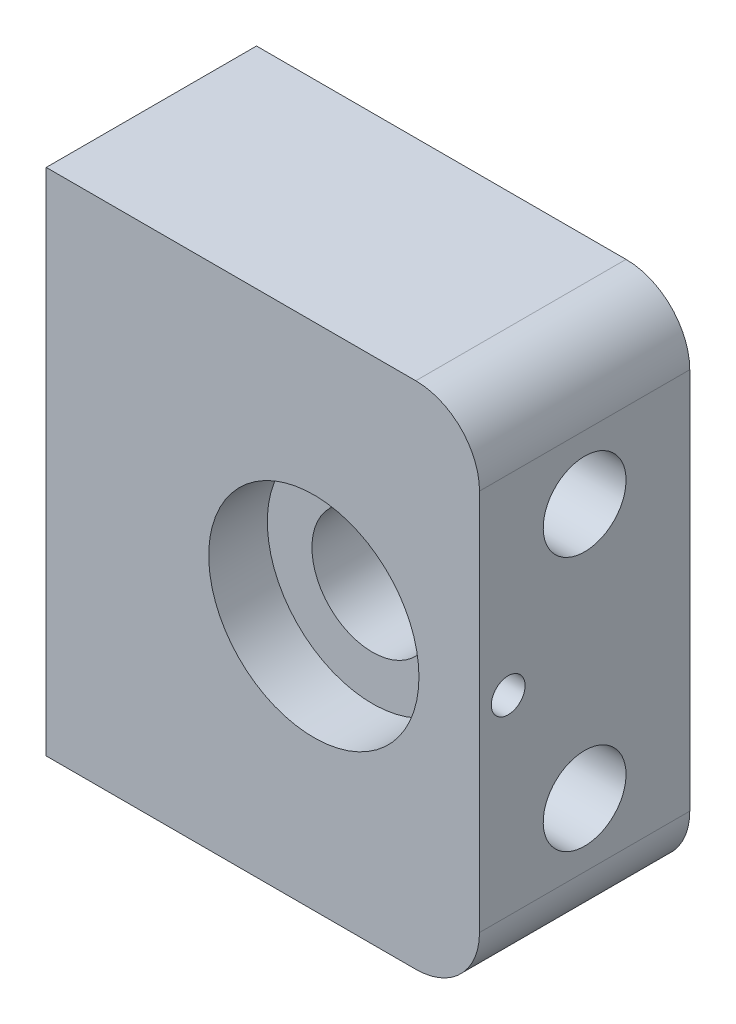
SolidWorks part; units mm, degrees
ref_plane "Alzado" through (0, 0, 0) normal (0, 0, 1) x (1, 0, 0)
ref_plane "Planta" through (0, 0, 0) normal (0, 1, 0) x (1, 0, 0)
ref_plane "Vista lateral" through (0, 0, 0) normal (1, 0, 0) x (0, 0, -1)
sketch "Croquis1" plane through (0, 0, 0) normal (0, 0, 1) x (1, 0, 0)
  line L1 (17, 20) -> (-17, 20)
  line L2 (17, 20) -> (17, -20)
  line L3 (17, -20) -> (-17, -20)
  line L4 (-17, 20) -> (-17, -20)
  line L5 (17, 20) -> (-17, -20) construction
  line L6 (17, -20) -> (-17, 20) construction
  circle A0 centre (4, 0) radius 4.75
  point P0 (0, 0)
  dimension "D3" = 9.5
  dimension "D1" = 40
  dimension "D2" = 21
  dimension "D4" = 34
extrude "Saliente-Extruir1" add sketch "Croquis1" along normal blind 16.5
sketch "Croquis2" plane through (0, 0, 16.5) normal (0, 0, 1) x (1, 0, 0)
  circle A0 centre (4, 0) radius 8.25
  dimension "D1" = 16.5
extrude "Cortar-Extruir1" cut sketch "Croquis2" against normal blind 4.6
sketch "Croquis3" plane through (17, 0, 0) normal (1, 0, 0) x (0, 0, -1)
  line L0 (-16.5, 0) -> (0, 0) construction
  line L1 (-16.5, -20) -> (-16.5, 20) construction
  circle A0 centre (-14.25, 0) radius 1.325
  point P7 (-14.1785, 0)
  dimension "D1" = 2.65
  dimension "D2" = 2.25
extrude "Cortar-Extruir2" cut sketch "Croquis3" against normal blind 5.6
sketch "Croquis4" plane through (17, 0, 0) normal (1, 0, 0) x (0, 0, -1)
  line L0 (-8.25, -20) -> (-8.25, 20) construction
  line L1 (-16.5, -20) -> (0, -20) construction
  line L2 (-16.5, 20) -> (0, 20) construction
  line L3 (-16.5, 0) -> (0, 0) construction
  line L4 (-16.5, -20) -> (-16.5, 20) construction
  circle A0 centre (-8.25, -10) radius 1.6
  circle A1 centre (-8.25, 10) radius 1.6
  dimension "D1" = 3.2
  dimension "D2" = 3.2
  dimension "D3" = 20
  dimension "D4" = 10
extrude "Cortar-Extruir3" cut sketch "Croquis4" against normal up to next
sketch "Croquis5" plane through (17, 0, 0) normal (1, 0, 0) x (0, 0, -1)
  circle A0 centre (-8.25, -10) radius 3.25
  circle A1 centre (-8.25, 10) radius 3.25
  dimension "D1" = 6.5
  dimension "D2" = 6.5
extrude "Cortar-Extruir4" cut sketch "Croquis5" against normal blind 28.6
fillet "Redondeo1" radius 5 2 edges at (17, -20, 8.25) (17, 20, 8.25)
